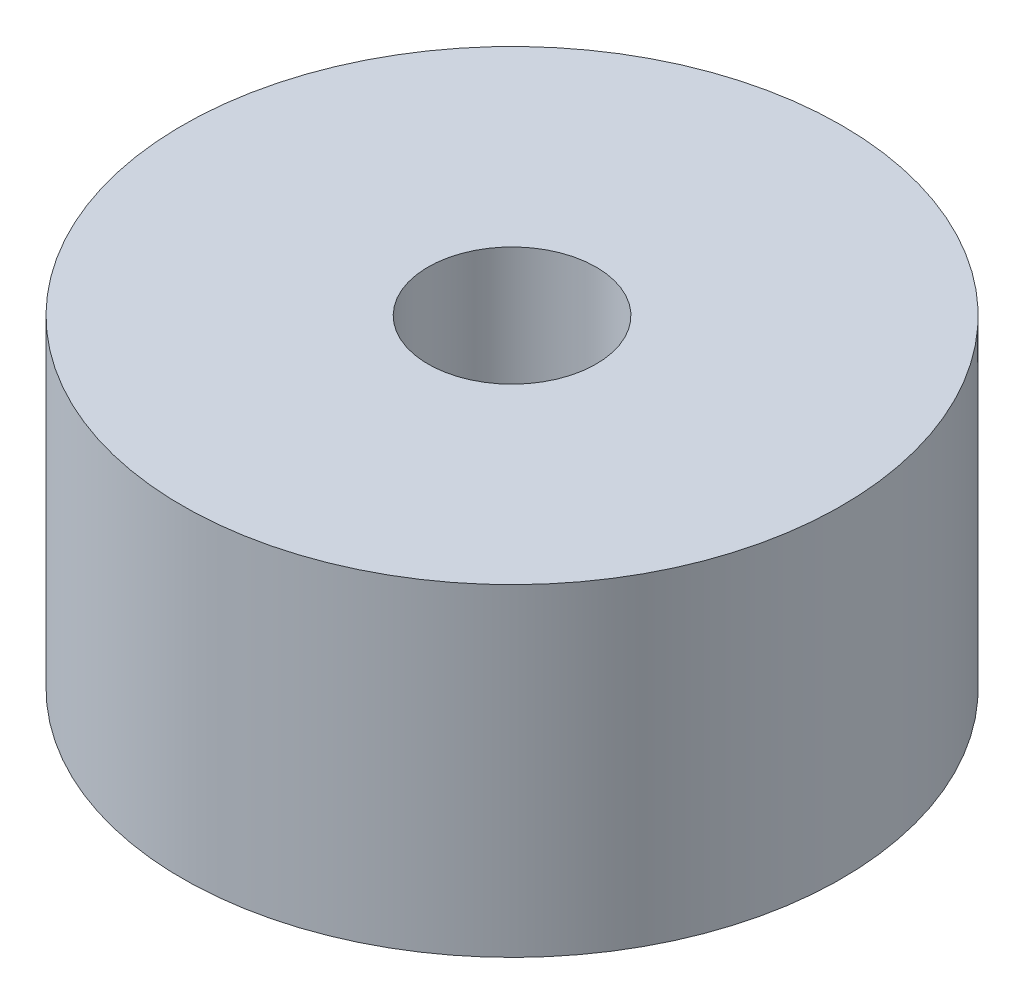
SolidWorks part; units mm, degrees
ref_plane "Front Plane" through (0, 0, 0) normal (0, 0, 1) x (1, 0, 0)
ref_plane "Top Plane" through (0, 0, 0) normal (0, 1, 0) x (1, 0, 0)
ref_plane "Right Plane" through (0, 0, 0) normal (1, 0, 0) x (0, 0, -1)
sketch "Sketch1" plane through (0, 0, 0) normal (0, 1, 0) x (1, 0, 0)
  circle A0 centre (0, 0) radius 6.223
  circle A1 centre (0, 0) radius 1.5875
  dimension "D1" = 3.175
  dimension "D2" = 12.446
extrude "Boss-Extrude1" add sketch "Sketch1" along normal blind 6.096
